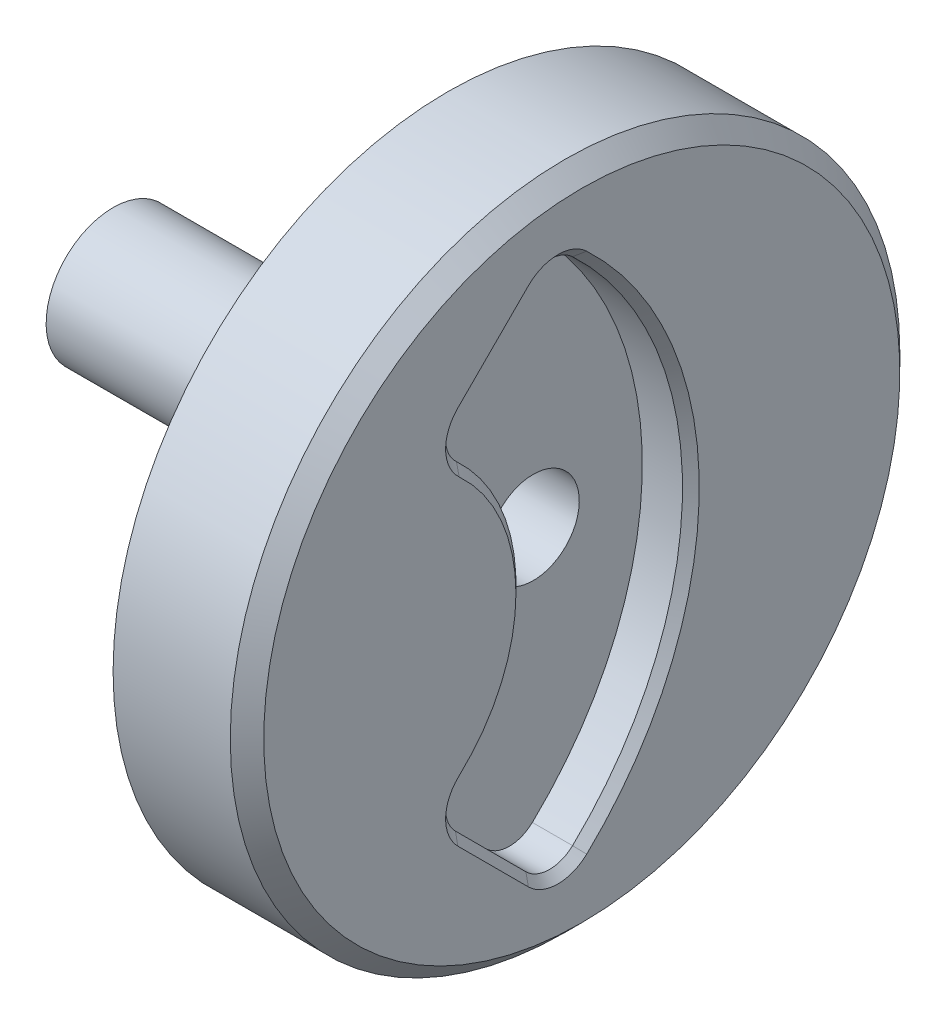
SolidWorks part; units mm, degrees
ref_plane "Alzado" through (0, 0, 0) normal (0, 0, 1) x (1, 0, 0)
ref_plane "Planta" through (0, 0, 0) normal (0, 1, 0) x (1, 0, 0)
ref_plane "Vista lateral" through (0, 0, 0) normal (1, 0, 0) x (0, 0, -1)
sketch "Croquis1" plane through (0, 0, 0) normal (0, 0, 1) x (1, 0, 0)
  line L0 (-20, 0) -> (-20, 4)
  line L1 (-20, 4) -> (0, 4)
  line L2 (0, 4) -> (0, 20)
  line L3 (0, 20) -> (8, 20)
  line L4 (8, 20) -> (8, 0)
  line L5 (8, 0) -> (-20, 0) construction
  line L6 (-20, 0) -> (8, 0)
  dimension "D1" = 40
  dimension "D2" = 8
  dimension "D3" = 20
  dimension "D4" = 8
revolve "Revolución1" add sketch "Croquis1" angle 360 about L5
sketch "Croquis2" plane through (8, 0, 0) normal (1, 0, 0) x (0, 0, -1)
  line L0 (0, 20) -> (0, -20) construction
  line L1 (-18.0333, 0) -> (-7.049, 10.9843) construction
  line L2 (-18.0333, 0) -> (-7.049, -10.9843) construction
  line L3 (-2.8392, 15.1941) -> (-7.049, 10.9843)
  line L4 (-7.049, -10.9843) -> (-2.8392, -15.1941)
  line L5 (-14.4333, 0) -> (-18.0333, 0) construction
  line L6 (-1.4538, 15.7797) -> (7.1943, 15.7797) construction
  line L7 (-1.4538, -15.7797) -> (8.9899, -15.7797) construction
  circle A0 centre (0, 0) radius 20 construction
  arc A1 (-0.0521, 15.2342) -> (-0.0521, -15.2342) centre (-14.4333, 0) cw
  arc A2 (-6.9884, 8.0978) -> (-6.9884, -8.0978) centre (-14.4333, 0) cw
  arc A3 (-0.0521, -15.2342) -> (-2.8392, -15.1941) centre (-1.425, -13.7799) cw
  arc A4 (-6.9884, -8.0978) -> (-7.049, -10.9843) centre (-5.6348, -9.5701) ccw
  arc A5 (-6.9884, 8.0978) -> (-7.049, 10.9843) centre (-5.6348, 9.5701) cw
  arc A6 (-0.0521, 15.2342) -> (-2.8392, 15.1941) centre (-1.425, 13.7799) ccw
  point P24 (-3.4333, 0)
  dimension "D1" = 20.95
  dimension "D2" = 11
  dimension "D4" = 2
  dimension "D3" = 90
  dimension "D5" = 3.6
extrude "Cortar-Extruir1" cut sketch "Croquis2" against normal blind 2.9
fillet "Redondeo1" radius 10 1 edges at (0, 4, 0)
sketch "Croquis3" plane through (-20, 0, 0) normal (-1, 0, 0) x (0, 0, 1)
  circle A0 centre (0, 0) radius 1.75
  dimension "D1" = 3.5
extrude "Cortar-Extruir2" cut sketch "Croquis3" against normal up to next
sketch "Croquis4" plane through (5.1, 0, 0) normal (1, 0, 0) x (0, 0, -1)
  circle A0 centre (0, 0) radius 2.75
  dimension "D1" = 5.5
extrude "Cortar-Extruir3" cut sketch "Croquis4" against normal offset from surface (22.1 mm away) 3 up to face at (-20, -1.75, 0)
chamfer "Chaflán1" distance 1 angle 45 1 edges at (8, 20, 0)
chamfer "Chaflán2" distance 0.5 angle 45 8 edges at (8, 0, 3.4333) (8, -9.5281, 7.6344) (8, 9.5281, 7.6344) (8, -13.0892, 4.9441) (8, 13.0892, 4.9441) (8, -15.7797, 1.4538) (8, 15.7797, 1.4538) (8, 0, -6.5167)
